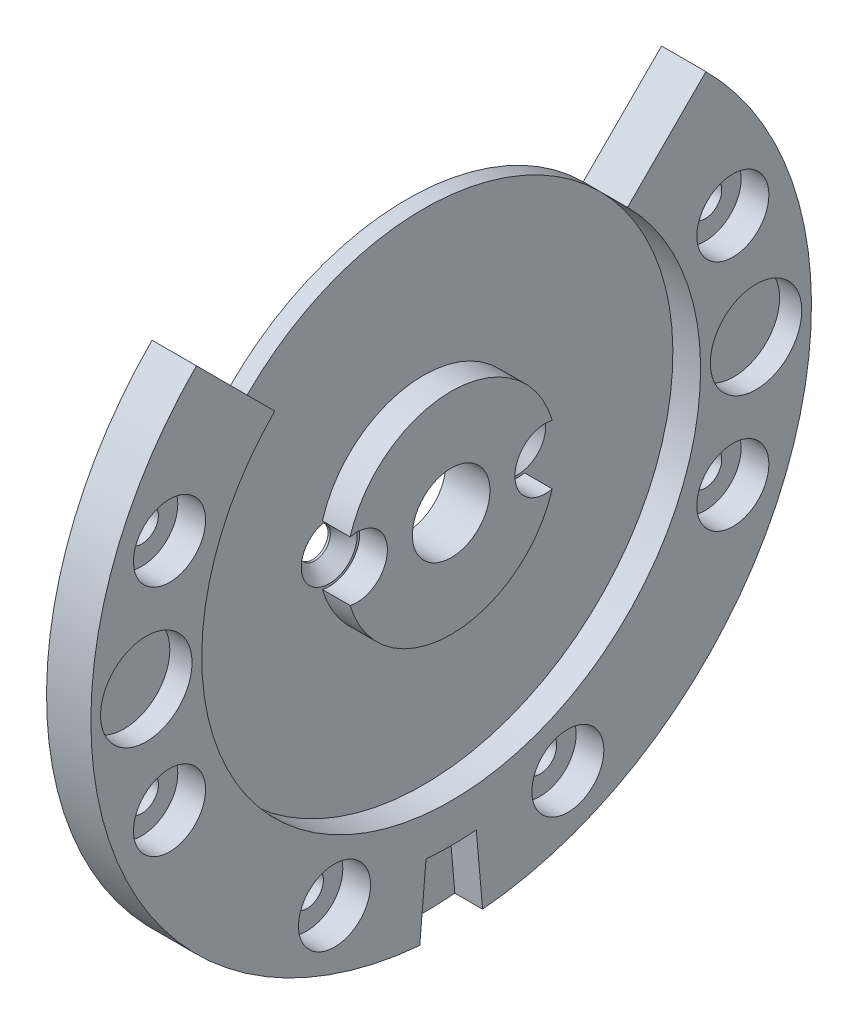
SolidWorks part; units mm, degrees
ref_plane "Alzado" through (0, 0, 0) normal (0, 0, 1) x (1, 0, 0)
ref_plane "Planta" through (0, 0, 0) normal (0, 1, 0) x (1, 0, 0)
ref_plane "Vista lateral" through (0, 0, 0) normal (1, 0, 0) x (0, 0, -1)
sketch "Croquis1" plane through (0, 0, 0) normal (0, 0, 1) x (1, 0, 0)
  line L0 (0, 0) -> (4, 0)
  line L1 (0, 0) -> (0, 32.5)
  line L2 (0, 32.5) -> (4, 32.5)
  line L3 (4, 32.5) -> (4, 22.5)
  line L4 (4, 22.5) -> (1.5, 22.5)
  line L5 (1.5, 22.5) -> (1.5, 9.5)
  line L6 (1.5, 9.5) -> (4, 9.5)
  line L7 (4, 9.5) -> (4, 0)
  dimension "D1" = 9.5
  dimension "D2" = 10
  dimension "D3" = 4
  dimension "D4" = 13
  dimension "D5" = 2.5
revolve "Revolución1" add sketch "Croquis1" angle 360 about L0
sketch "Croquis2" plane through (4, 0, 0) normal (1, 0, 0) x (0, 0, -1)
  circle A0 centre (0, 0) radius 8.5
  circle A1 centre (8.5, 0) radius 1.25
  circle A2 centre (-8.5, 0) radius 1.25
  circle A3 centre (0, 0) radius 3.5
  circle A4 centre (0, 0) radius 27.5
  circle A5 centre (27.5, 0) radius 1.5
  circle A6 centre (25.4067, -10.5238) radius 1.5
  circle A7 centre (19.4454, -19.4454) radius 1.5
  circle A8 centre (10.5238, -25.4067) radius 1.5
  circle A9 centre (0, -27.5) radius 1.5
  circle A10 centre (-10.5238, -25.4067) radius 1.5
  circle A11 centre (-19.4454, -19.4454) radius 1.5
  circle A12 centre (-25.4067, -10.5238) radius 1.5
  circle A13 centre (-27.5, 0) radius 1.5
  circle A14 centre (-25.4067, 10.5238) radius 1.5
  circle A15 centre (-19.4454, 19.4454) radius 1.5
  circle A16 centre (-10.5238, 25.4067) radius 1.5
  circle A17 centre (0, 27.5) radius 1.5
  circle A18 centre (10.5238, 25.4067) radius 1.5
  circle A19 centre (19.4454, 19.4454) radius 1.5
  circle A20 centre (25.4067, 10.5238) radius 1.5
  point P9 (0, 0)
  point P45 (0, 0)
  dimension "D1" = 2
  dimension "D2" = 17
  dimension "D3" = 2.5
  dimension "D4" = 7
  dimension "D5" = 16
  dimension "D6" = 55
  dimension "D7" = 3
extrude "Cortar-Extruir1" cut sketch "Croquis2" against normal blind 4 contours A14 | A12 | A10 | A8 | A6 | A20 | A3
sketch "Croquis3" plane through (4, 0, 0) normal (1, 0, 0) x (0, 0, -1)
  line L0 (0, 0) -> (-22.981, 22.981)
  line L1 (-22.981, 22.981) -> (0, 0)
  line L2 (0, 0) -> (22.981, 22.981)
  line L3 (-32.5, 0) -> (32.5, 0)
  circle A0 centre (0, 0) radius 32.5 construction
  circle M1 centre (0, 0) radius 32.5
  circle M2 centre (0, 0) radius 22.5
  dimension "D1" = 45
  dimension "D2" = 45
extrude "Cortar-Extruir2" cut sketch "Croquis3" against normal blind 10 contours L2 L0 M2 M1
sketch "Croquis4" plane through (4, 0, 0) normal (1, 0, 0) x (0, 0, -1)
  line L0 (0, 0) -> (2.8326, -32.3763)
  line L1 (0, 0) -> (-2.8326, -32.3763)
  line L2 (-32.5, 0) -> (32.5, 0)
  arc A0 (-22.981, 22.981) -> (22.981, 22.981) centre (0, 0) ccw construction
  circle A1 centre (0, 0) radius 26
  circle A2 centre (0, 0) radius 32.5
  arc M2 (-22.981, 22.981) -> (22.981, 22.981) centre (0, 0) ccw
  arc M4 (15.9099, 15.9099) -> (-15.9099, 15.9099) centre (0, 0) cw
  dimension "D3" = 65
  dimension "D4" = 52
  dimension "D1" = 85
  dimension "D2" = 85
extrude "Cortar-Extruir3" cut sketch "Croquis4" against normal blind 2.5 contours L1 L0 M4 M2
sketch "Croquis5" plane through (4, 0, 0) normal (1, 0, 0) x (0, 0, -1)
  line L0 (22.5, 0) -> (32.5, 0)
  line L1 (-22.5, 0) -> (-32.5, 0)
  arc A0 (-15.9099, 15.9099) -> (15.9099, 15.9099) centre (0, 0) ccw construction
  arc A1 (-15.9099, 15.9099) -> (15.9099, 15.9099) centre (0, 0) ccw construction
  arc A2 (2.8326, -32.3763) -> (22.981, 22.981) centre (0, 0) ccw construction
  arc A3 (-15.9099, 15.9099) -> (15.9099, 15.9099) centre (0, 0) ccw construction
  arc A4 (-15.9099, 15.9099) -> (15.9099, 15.9099) centre (0, 0) ccw construction
  arc A5 (-22.981, 22.981) -> (-2.8326, -32.3763) centre (0, 0) ccw construction
  circle A6 centre (27.5, 0) radius 4.125
  circle A7 centre (-27.5, 0) radius 4.125
  dimension "D1" = 8.25
  dimension "D2" = 8.25
  dimension "D3" = 27.5
extrude "Cortar-Extruir4" cut sketch "Croquis5" against normal blind 2 contours L0 A6 | L0 A6 | L1 A7 | L1 A7
sketch "Croquis7" plane through (4, 0, 0) normal (1, 0, 0) x (0, 0, -1)
  circle A0 centre (0, 0) radius 8.5
  circle A1 centre (8.5, 0) radius 2.75
  circle A2 centre (-8.5, 0) radius 2.75
  circle A3 centre (0, 0) radius 27.5
  circle A4 centre (27.5, 0) radius 3.25
  circle A5 centre (25.4067, -10.5238) radius 3.25
  circle A6 centre (19.4454, -19.4454) radius 3.25
  circle A7 centre (10.5238, -25.4067) radius 3.25
  circle A8 centre (0, -27.5) radius 3.25
  circle A9 centre (-10.5238, -25.4067) radius 3.25
  circle A10 centre (-19.4454, -19.4454) radius 3.25
  circle A11 centre (-25.4067, -10.5238) radius 3.25
  circle A12 centre (-27.5, 0) radius 3.25
  circle A13 centre (-25.4067, 10.5238) radius 3.25
  circle A14 centre (-19.4454, 19.4454) radius 3.25
  circle A15 centre (-10.5238, 25.4067) radius 3.25
  circle A16 centre (0, 27.5) radius 3.25
  circle A17 centre (10.5238, 25.4067) radius 3.25
  circle A18 centre (19.4454, 19.4454) radius 3.25
  circle A19 centre (25.4067, 10.5238) radius 3.25
  point P10 (0, 0)
  point P44 (0, 0)
  dimension "D1" = 2
  dimension "D2" = 5.5
  dimension "D3" = 17
  dimension "D4" = 55
  dimension "D5" = 6.5
  dimension "D6" = 16
extrude "Cortar-Extruir6" cut sketch "Croquis7" against normal blind 2.5 contours A13 | A11 | A9 | A7 | A5 | A19 | A1 | A2
sketch "Croquis8" plane through (1.5, 0, 0) normal (1, 0, 0) x (0, 0, -1)
  line L0 (-8.5, 0) -> (8.5, 0)
  circle A0 centre (0, 0) radius 8.5
  dimension "D1" = 17
hole_wizard "Avellanado para tornillo con cabeza ovalada de #31" positions "Croquis3D2" profile "Croquis10" countersink size "#3" standard "Ansi Inch" end condition through all
sketch3d "Croquis3D2"
  point P0 (1.5, 0, 8.5)
  point P3 (1.5, 0, -8.5)
sketch "Croquis10" plane through (1.5, 0, 8.5) normal (0, 1, 0) x (0, 0, -1)
  line L0 (0, 0) -> (0, 1.5)
  line L1 (0, 1.5) -> (1.397, 1.5)
  line L2 (1.397, 1.5) -> (1.397, 1.3003)
  line L3 (1.397, 1.3003) -> (2.5273, 0)
  line L5 (2.5273, 0) -> (0, 0)
  line L6 (-1.397, 1.3003) -> (-2.5273, 0) construction
  line L11 (0, -6.35) -> (0, 107.95) construction
  dimension "Diámetro de taladro hasta el siguiente" = 2.794
  dimension "Profundidad de taladro hasta el siguiente" = 1.5
  dimension "Diámetro de avellanado cercano" = 5.0546
  dimension "Ángulo de avellanado cercano" = 82
